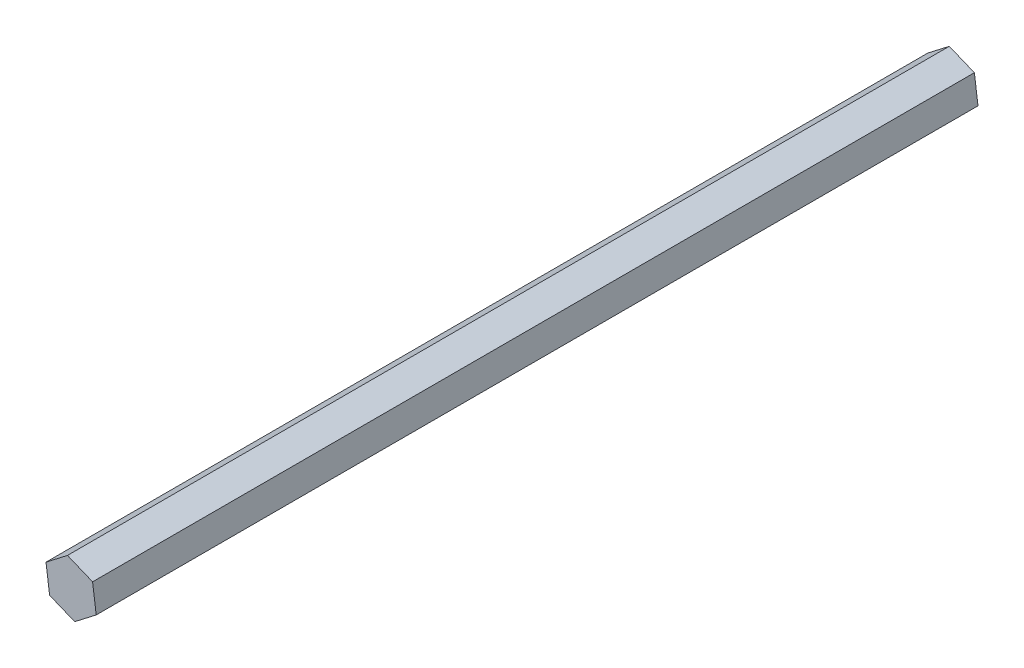
SolidWorks part; units mm, degrees
ref_plane "Front Plane" through (0, 0, 0) normal (0, 0, 1) x (1, 0, 0)
ref_plane "Top Plane" through (0, 0, 0) normal (0, 1, 0) x (1, 0, 0)
ref_plane "Right Plane" through (0, 0, 0) normal (1, 0, 0) x (0, 0, -1)
sketch "Sketch1" plane through (0, 0, 0) normal (0, 0, 1) x (1, 0, 0)
  line L1 (5.8042, 4.4804) -> (-0.9781, 7.2668)
  line L2 (-0.9781, 7.2668) -> (-6.7823, 2.7864)
  line L3 (-6.7823, 2.7864) -> (-5.8042, -4.4804)
  line L4 (-5.8042, -4.4804) -> (0.9781, -7.2668)
  line L5 (0.9781, -7.2668) -> (6.7823, -2.7864)
  line L6 (6.7823, -2.7864) -> (5.8042, 4.4804)
  circle A0 centre (0, 0) radius 6.35 construction
  dimension "D1" = 12.7
extrude "Boss-Extrude1" add sketch "Sketch1" along normal blind 254
sketch "Sketch2" plane through (0, 0, 0) normal (0, 0, -1) x (-1, 0, 0)
  line L1 (-13.8118, -13.2616) -> (10.2198, -13.2616)
  line L2 (-13.8118, -13.2616) -> (-13.8118, 7.2668)
  line L3 (-13.8118, 7.2668) -> (10.2198, 7.2668)
  line L4 (10.2198, -13.2616) -> (10.2198, 7.2668)
extrude "Cut-Extrude1" cut sketch "Sketch2" against normal blind 15.748
